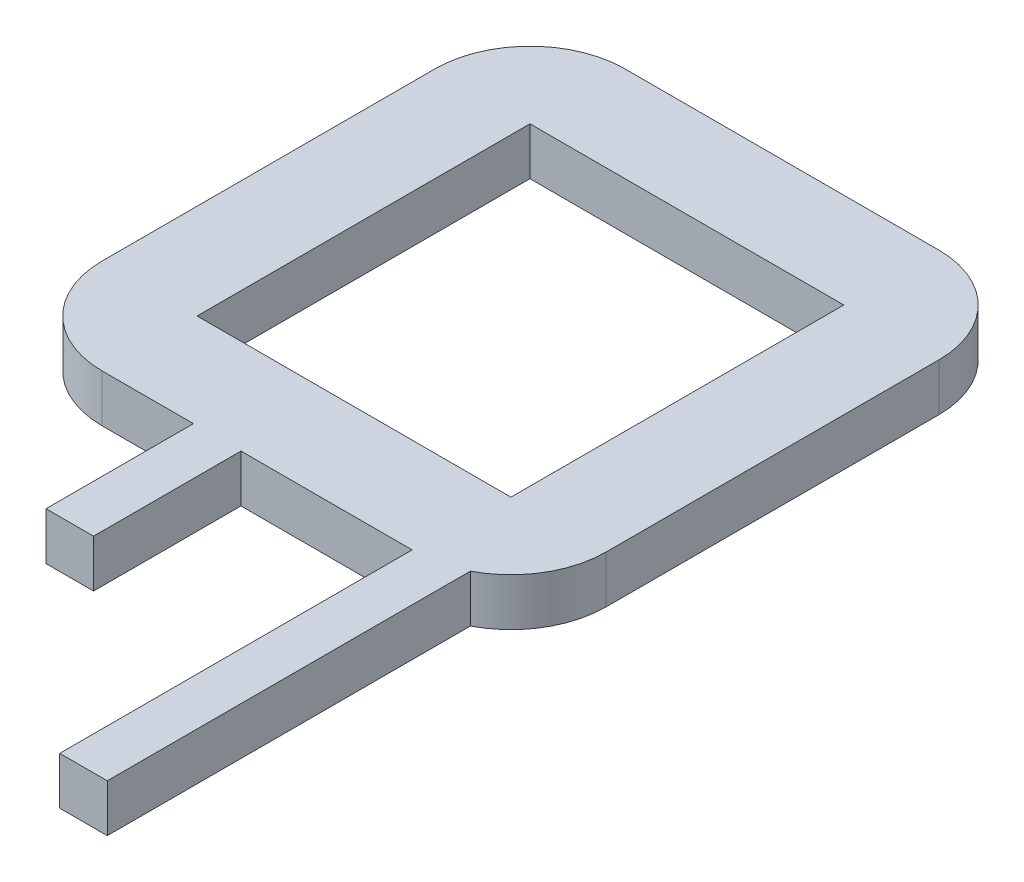
SolidWorks part; units mm, degrees
ref_plane "前基準面" through (0, 0, 0) normal (0, 0, 1) x (1, 0, 0)
ref_plane "上基準面" through (0, 0, 0) normal (0, 1, 0) x (1, 0, 0)
ref_plane "右基準面" through (0, 0, 0) normal (1, 0, 0) x (0, 0, -1)
sketch "草圖1" plane through (0, 0, 0) normal (0, 1, 0) x (1, 0, 0)
  line L0 (-16.5, 17.5) -> (-26.5, 17.5) construction
  line L1 (16.5, -17.5) -> (-16.5, -17.5)
  line L2 (16.5, -17.5) -> (16.5, 17.5)
  line L3 (16.5, 17.5) -> (-16.5, 17.5)
  line L4 (-16.5, -17.5) -> (-16.5, 17.5)
  line L5 (0, 17.5) -> (0, -17.5) construction
  line L6 (16.5, 0) -> (-16.5, 0) construction
  line L7 (16.5, -27.5) -> (-16.5, -27.5)
  line L8 (26.5, -17.5) -> (26.5, 17.5)
  line L9 (16.5, 27.5) -> (-16.5, 27.5)
  line L10 (-26.5, -17.5) -> (-26.5, 17.5)
  line L11 (0, 27.5) -> (0, -27.5) construction
  line L12 (26.5, 0) -> (-26.5, 0) construction
  line L13 (-16.5, 17.5) -> (-16.5, 27.5) construction
  line L14 (16.5, 17.5) -> (16.5, 27.5) construction
  line L15 (16.5, 17.5) -> (26.5, 17.5) construction
  line L16 (16.1075, -24.555) -> (16.1075, -64.555)
  line L21 (21.1075, -64.555) -> (16.1075, -64.555)
  line L22 (21.1075, -64.555) -> (21.1075, -24.555)
  line L23 (-1.8925, -27.5) -> (-6.8925, -27.5)
  line L24 (-1.8925, -27.5) -> (-1.8925, -43)
  line L25 (-1.8925, -43) -> (-6.8925, -43)
  line L26 (-6.8925, -27.5) -> (-6.8925, -43)
  line L27 (21.1075, -24.555) -> (16.1075, -24.555)
  arc A0 (-26.5, 17.5) -> (-16.5, 27.5) centre (-16.5, 17.5) cw
  arc A1 (16.5, 27.5) -> (26.5, 17.5) centre (16.5, 17.5) cw
  arc A2 (-26.5, -17.5) -> (-16.5, -27.5) centre (-16.5, -17.5) ccw
  arc A3 (16.5, -27.5) -> (26.5, -17.5) centre (16.5, -17.5) ccw
  point P0 (0, 0)
  point P4 (0, 0)
  dimension "D1" = 33
  dimension "D2" = 35
  dimension "D3" = 18
  dimension "D4" = 5
  dimension "D5" = 5
  dimension "D6" = 40
  dimension "D7" = 15.5
extrude "填料-伸長1" add sketch "草圖1" along normal blind 5 contours L7 A3 L8 A1 L9 A0 L10 A2 L1 L4 L3 L2 | L7 L26 L25 L24 | L22 L27 L7 L16 L21 | L7 A3 L22 L27 L16
